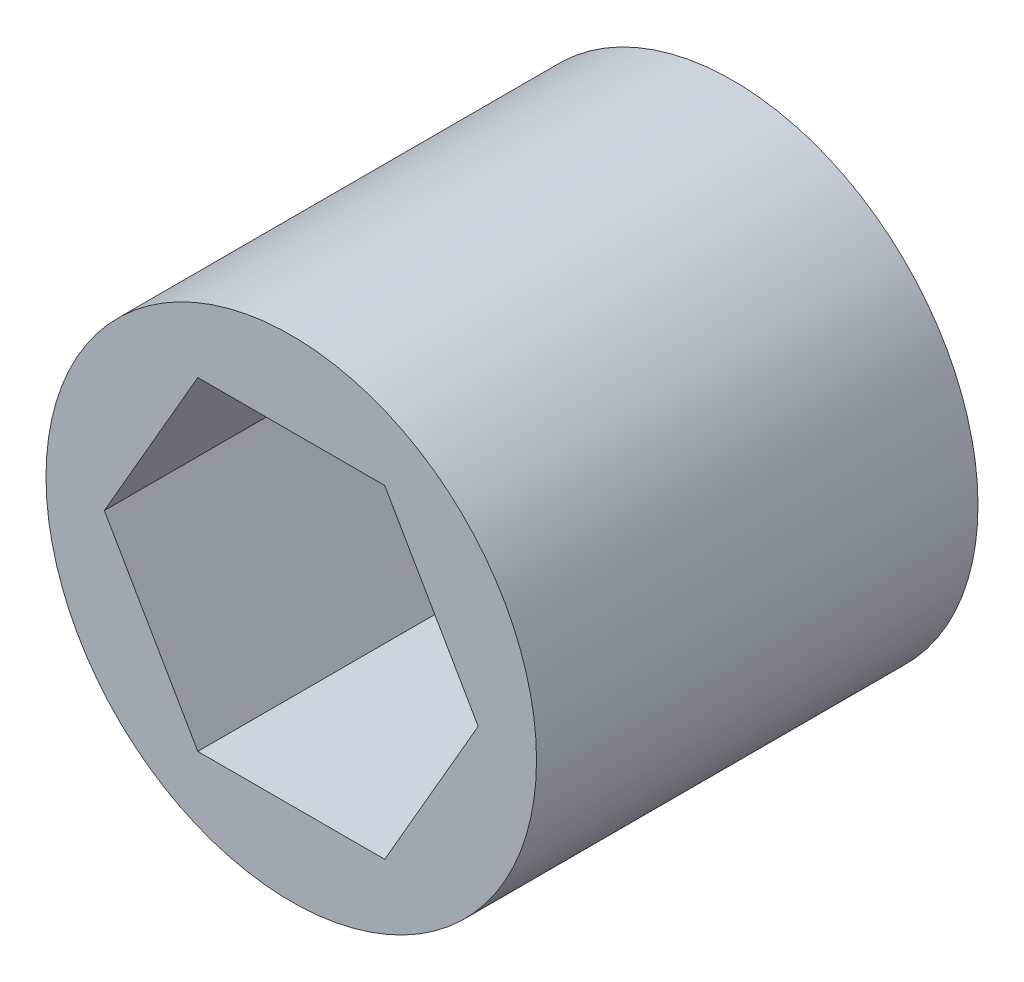
SolidWorks part; units mm, degrees
ref_plane "Front Plane" through (0, 0, 0) normal (0, 0, 1) x (1, 0, 0)
ref_plane "Top Plane" through (0, 0, 0) normal (0, 1, 0) x (1, 0, 0)
ref_plane "Right Plane" through (0, 0, 0) normal (1, 0, 0) x (0, 0, -1)
sketch "Sketch1" plane through (0, 0, 0) normal (0, 0, 1) x (1, 0, 0)
  line L1 (-7.621, 0) -> (-3.8105, -6.6)
  line L2 (-3.8105, -6.6) -> (3.8105, -6.6)
  line L3 (3.8105, -6.6) -> (7.621, 0)
  line L4 (7.621, 0) -> (3.8105, 6.6)
  line L5 (3.8105, 6.6) -> (-3.8105, 6.6)
  line L6 (-3.8105, 6.6) -> (-7.621, 0)
  circle A0 centre (0, 0) radius 10
  circle A1 centre (0, 0) radius 6.6 construction
  dimension "D1" = 13.2
  dimension "D2" = 20
extrude "Boss-Extrude1" add sketch "Sketch1" along normal blind 18
